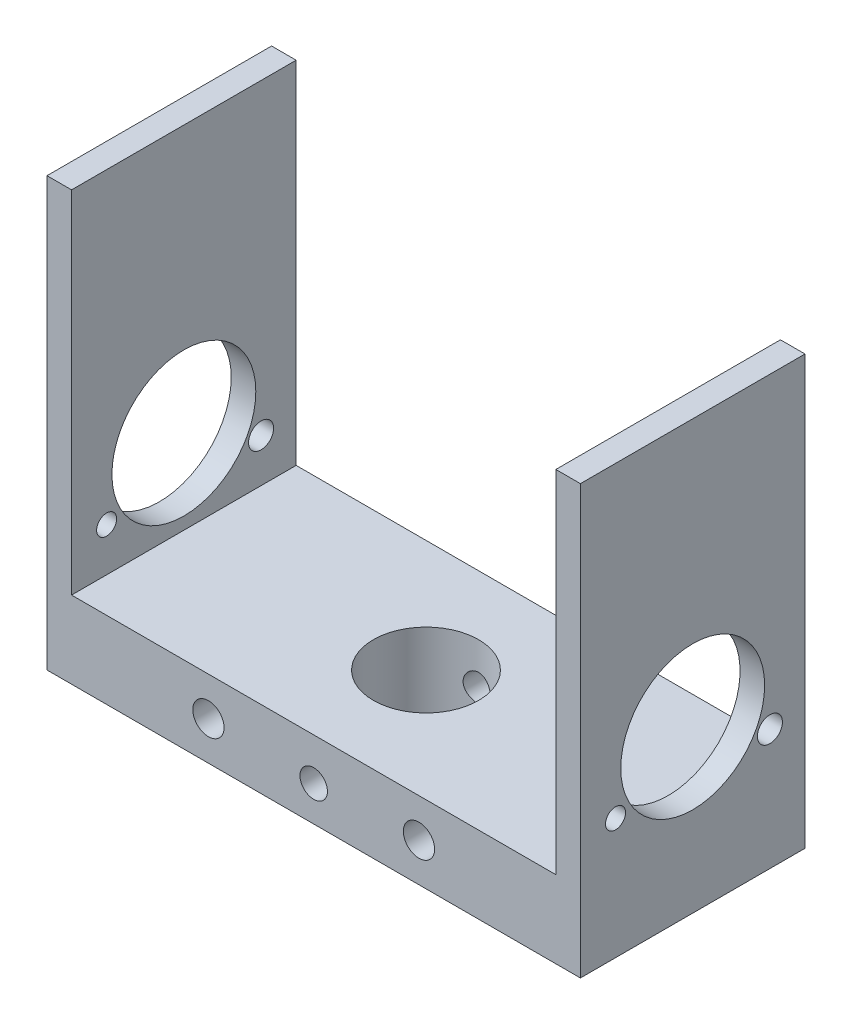
SolidWorks part; units mm, degrees
ref_plane "Front Plane" through (0, 0, 0) normal (0, 0, 1) x (1, 0, 0)
ref_plane "Top Plane" through (0, 0, 0) normal (0, 1, 0) x (1, 0, 0)
ref_plane "Right Plane" through (0, 0, 0) normal (1, 0, 0) x (0, 0, -1)
sketch "Sketch1" plane through (0, 0, 0) normal (0, 1, 0) x (1, 0, 0)
  line L1 (0, 16) -> (38, 16)
  line L2 (0, 16) -> (0, -16)
  line L3 (0, -16) -> (38, -16)
  line L4 (38, 16) -> (38, -16)
  circle A0 centre (0, 0) radius 7.5
  dimension "D1" = 15
  dimension "D2" = 16
  dimension "D3" = 16
  dimension "D4" = 38
extrude "Boss-Extrude1" add sketch "Sketch1" along normal blind 11 contours A0 L2 L3 L4 L1
sketch "Sketch2" plane through (0, 11, 0) normal (0, 1, 0) x (1, 0, 0)
  line L0 (0, -16) -> (38, -16) construction
  line L1 (38, 16) -> (34.5, 16)
  line L2 (38, 16) -> (38, -16)
  line L3 (38, -16) -> (34.5, -16)
  line L4 (34.5, 16) -> (34.5, -16)
  line L5 (0, -7.5) -> (0, -16) construction
  dimension "D1" = 34.5
extrude "Boss-Extrude2" add sketch "Sketch2" along normal blind 50
sketch "Sketch3" plane through (34.5, 0, 0) normal (-1, 0, 0) x (0, 0, 1)
  line L0 (-16, 11) -> (16, 11) construction
  circle A0 centre (0, 23) radius 10.25
  circle A1 centre (-11, 17.2028) radius 1.7836
  circle A2 centre (11, 17.2028) radius 1.4262
  dimension "D1" = 20.5
  dimension "D2" = 12
  dimension "D3" = 11
  dimension "D4" = 11
extrude "Cut-Extrude1" cut sketch "Sketch3" against normal blind 50
sketch "Sketch4" plane through (0, 0, -16) normal (0, 0, -1) x (-1, 0, 0)
  line L0 (0, 11) -> (0, 0) construction
  line L1 (0, 11) -> (-34.5, 11) construction
  circle A0 centre (-15, 5.5) radius 2.2265
  dimension "D1" = 5.5
  dimension "D2" = 15
extrude "Cut-Extrude2" cut sketch "Sketch4" against normal blind 36
mirror "Mirror1" about plane through (0, 11, 0) normal (1, 0, 0) of "Cut-Extrude2", "Boss-Extrude1", "Boss-Extrude2", "Cut-Extrude1"
sketch "Sketch5" plane through (0, 0, 16) normal (0, 0, 1) x (1, 0, 0)
  line L0 (-38, 0) -> (38, 0) construction
  circle A0 centre (0, 5) radius 1.9566
  dimension "D1" = 5
extrude "Cut-Extrude3" cut sketch "Sketch5" against normal blind 32
